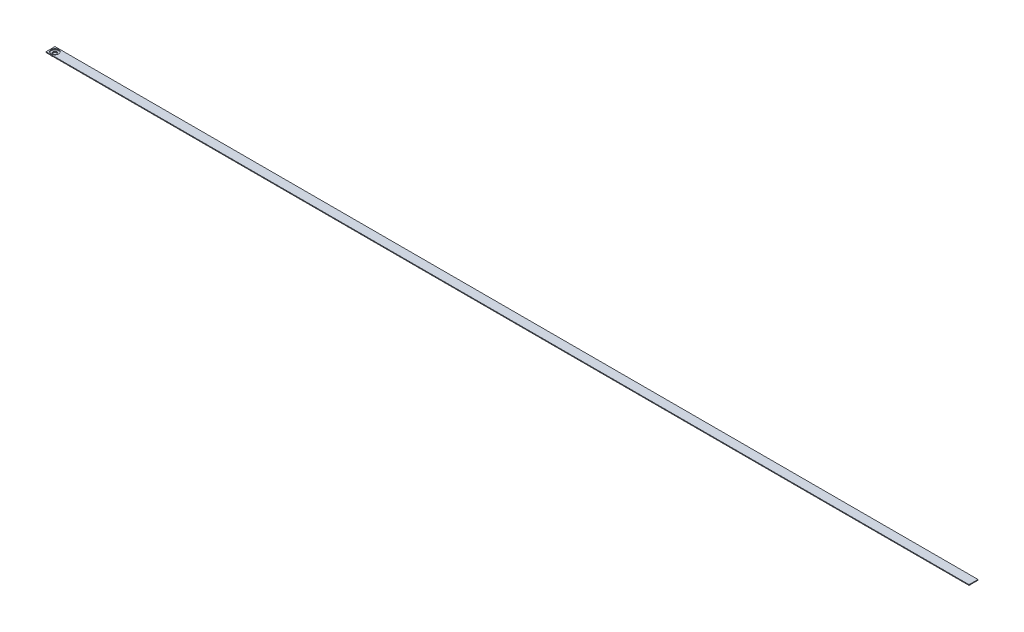
SolidWorks part; units mm, degrees
material "Galvanized Steel"
ref_plane "Front Plane" through (0, 0, 0) normal (0, 0, 1) x (1, 0, 0)
ref_plane "Top Plane" through (0, 0, 0) normal (0, 1, 0) x (1, 0, 0)
ref_plane "Right Plane" through (0, 0, 0) normal (1, 0, 0) x (0, 0, -1)
sketch "Sketch1" plane through (0, 0, 0) normal (0, 1, 0) x (1, 0, 0)
  line L1 (-1225, -11.9) -> (1225, -11.9)
  line L2 (-1225, -11.9) -> (-1225, 11.9)
  line L3 (-1225, 11.9) -> (1225, 11.9)
  line L4 (1225, -11.9) -> (1225, 11.9)
  line L5 (-1225, -11.9) -> (1225, 11.9) construction
  line L6 (-1225, 11.9) -> (1225, -11.9) construction
  point P0 (0, 0)
  dimension "D1" = 23.8
  dimension "D2" = 2450
extrude "Boss-Extrude1" add sketch "Sketch1" along normal mid plane 1.9
ref_plane "Plane1" through (0, -2.8, 0) normal (0, 1, 0) x (1, 0, 0)
ref_plane "Plane2" through (0, -5.6, 0) normal (0, 1, 0) x (1, 0, 0)
sketch "Sketch3" plane through (0, 0.95, 0) normal (0, 1, 0) x (1, 0, 0)
  line L0 (-1.045, 0) -> (1.045, 0) construction
  line L1 (-1225, 11.9) -> (-1225, -11.9) construction
  circle A0 centre (-1213.1, 0) radius 10
  dimension "D1" = 1.9
  dimension "D2" = 20
extrude "Cut-Extrude1" cut sketch "Sketch3" against normal up to next
sketch "Sketch4" plane through (0, -2.8, 0) normal (0, 1, 0) x (1, 0, 0)
  circle A0 centre (-1213.1, 0) radius 10 construction
  circle A1 centre (-1213.1, 0) radius 10
  circle A2 centre (-1213.1, 0) radius 5.25
  dimension "D1" = 10.5
extrude "Boss-Extrude3" add sketch "Sketch4" along normal mid plane 1.9 separate body
sketch "Sketch5" plane through (0, -5.6, 0) normal (0, 1, 0) x (1, 0, 0)
  circle A0 centre (-1213.1, 0) radius 5.25 construction
  circle A1 centre (-1213.1, 0) radius 5.25
extrude "Boss-Extrude4" add sketch "Sketch5" along normal mid plane 1.9 separate body
